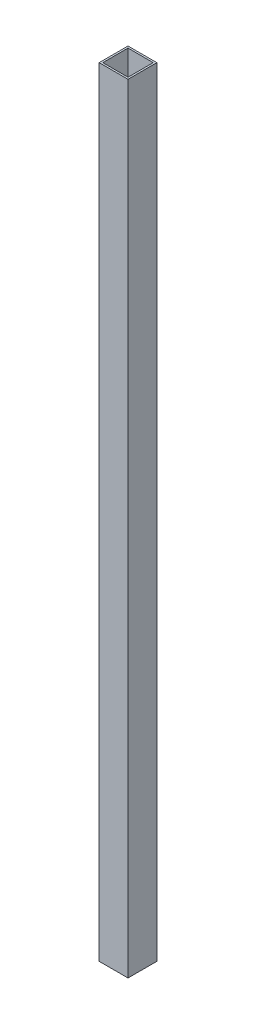
SolidWorks part; units mm, degrees
ref_plane "Front Plane" through (0, 0, 0) normal (0, 0, 1) x (1, 0, 0)
ref_plane "Top Plane" through (0, 0, 0) normal (0, 1, 0) x (1, 0, 0)
ref_plane "Right Plane" through (0, 0, 0) normal (1, 0, 0) x (0, 0, -1)
sketch "Sketch1" plane through (0, 0, 0) normal (0, 1, 0) x (1, 0, 0)
  line L1 (12.7, 12.7) -> (-12.7, 12.7)
  line L2 (12.7, 12.7) -> (12.7, -12.7)
  line L3 (12.7, -12.7) -> (-12.7, -12.7)
  line L4 (-12.7, 12.7) -> (-12.7, -12.7)
  line L5 (12.7, 12.7) -> (-12.7, -12.7) construction
  line L6 (12.7, -12.7) -> (-12.7, 12.7) construction
  line L7 (11.1125, 11.1125) -> (-11.1125, 11.1125)
  line L8 (11.1125, 11.1125) -> (11.1125, -11.1125)
  line L9 (11.1125, -11.1125) -> (-11.1125, -11.1125)
  line L10 (-11.1125, 11.1125) -> (-11.1125, -11.1125)
  line L11 (11.1125, 11.1125) -> (-11.1125, -11.1125) construction
  line L12 (11.1125, -11.1125) -> (-11.1125, 11.1125) construction
  point P0 (0, 0)
  point P6 (0, 0)
  dimension "D1" = 25.4
  dimension "D2" = 25.4
  dimension "D3" = 1.5875
  dimension "D4" = 1.5875
extrude "Boss-Extrude1" add sketch "Sketch1" along normal blind 685.8
